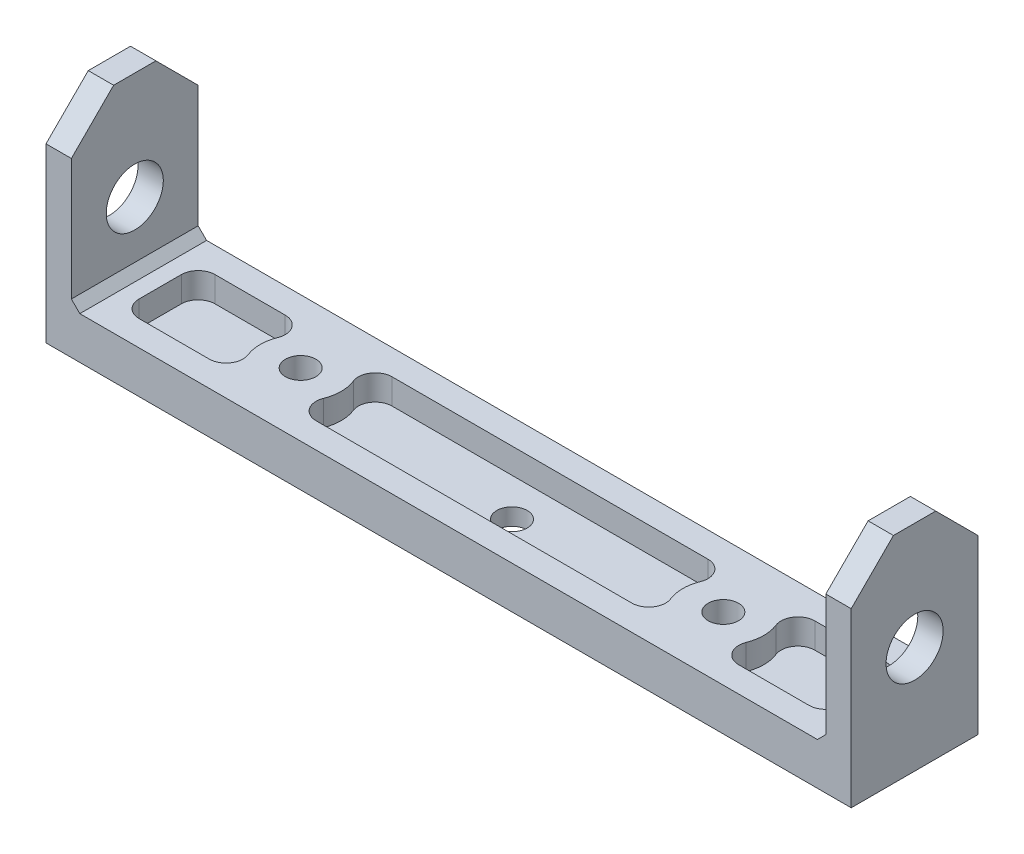
SolidWorks part; units mm, degrees
ref_plane "Front Plane" through (0, 0, 0) normal (0, 0, 1) x (1, 0, 0)
ref_plane "Top Plane" through (0, 0, 0) normal (0, 1, 0) x (1, 0, 0)
ref_plane "Right Plane" through (0, 0, 0) normal (1, 0, 0) x (0, 0, -1)
sketch "Sketch1" plane through (0, 0, 0) normal (0, 1, 0) x (1, 0, 0)
  line L1 (-47.625, -7.5) -> (47.625, -7.5)
  line L2 (-47.625, -7.5) -> (-47.625, 7.5)
  line L3 (-47.625, 7.5) -> (47.625, 7.5)
  line L4 (47.625, -7.5) -> (47.625, 7.5)
  line L5 (-47.625, -7.5) -> (47.625, 7.5) construction
  line L6 (-47.625, 7.5) -> (47.625, -7.5) construction
  point P0 (0, 0)
  dimension "D1" = 95.25
  dimension "D2" = 15
extrude "Boss-Extrude1" add sketch "Sketch1" along normal blind 5
sketch "Sketch2" plane through (0, 0, 7.5) normal (0, 0, 1) x (1, 0, 0)
  line L1 (-47.625, 0) -> (-44.625, 0)
  line L2 (-47.625, 0) -> (-47.625, 25.4)
  line L3 (-47.625, 25.4) -> (-44.625, 25.4)
  line L4 (-44.625, 0) -> (-44.625, 25.4)
  dimension "D1" = 25.4
  dimension "D2" = 3
extrude "Boss-Extrude2" add sketch "Sketch2" against normal through all
hole_wizard "1/4 Clearance Hole1" positions "Sketch3" profile "Sketch4" hole size "1/4" standard "ANSI Inch"
sketch "Sketch3" plane through (-44.625, 0, 0) normal (1, 0, 0) x (0, 0, -1)
  line L0 (-7.5, 5) -> (-7.5, 25.4) construction
  line L1 (7.5, 25.4) -> (-7.5, 25.4) construction
  point P0 (0, 12.7)
  dimension "D1" = 7.5
  dimension "D2" = 12.7
sketch "Sketch4" plane through (-44.625, 12.7, 0) normal (0, 1, 0) x (0, 0, -1)
  line L0 (0, 0) -> (0, 14.0298)
  line L1 (0, 14.0298) -> (3.3782, 12)
  line L2 (3.3782, 12) -> (3.3782, 0)
  line L5 (3.3782, 0) -> (0, 0)
  line L10 (0, 14.0298) -> (-3.3782, 12) construction
  line L11 (0, -6.35) -> (0, 107.95) construction
  dimension "Hole Dia." = 6.7564
  dimension "Hole Depth" = 12
  dimension "Drill Angle" = 118
hole_wizard "M3 Clearance Hole1" positions "Sketch7" profile "Sketch8" hole size "M3" standard "ANSI Metric"
sketch "Sketch7" plane through (0, 5, 0) normal (0, 1, 0) x (1, 0, 0)
  point P0 (-25, 0)
  point P3 (0, 0)
  point P7 (0, 0)
  point P8 (0, 0)
  dimension "D1" = 25
sketch "Sketch8" plane through (-25, 5, 0) normal (1, 0, 0) x (0, 0, 1)
  line L0 (0, 0) -> (0, 13.0815)
  line L1 (0, 13.0815) -> (1.8, 12)
  line L2 (1.8, 12) -> (1.8, 0)
  line L5 (1.8, 0) -> (0, 0)
  line L10 (0, 13.0815) -> (-1.8, 12) construction
  line L11 (0, -6.35) -> (0, 107.95) construction
  dimension "Hole Dia." = 3.6
  dimension "Hole Depth" = 12
  dimension "Drill Angle" = 118
sketch "Sketch9" plane through (0, 5, 0) normal (0, 1, 0) x (1, 0, 0)
  line L8 (44.625, 4.5) -> (-41.625, 4.5)
  line L9 (-41.625, 4.5) -> (-41.625, -4.5)
  line L10 (-41.625, -4.5) -> (44.625, -4.5)
  line L11 (44.625, -4.5) -> (44.625, 4.5)
  line L12 (44.625, 4.5) -> (-41.625, 4.5)
  line L13 (-41.625, 4.5) -> (-41.625, -4.5)
  line L14 (-41.625, -4.5) -> (44.625, -4.5)
  line L15 (44.625, -4.5) -> (44.625, 4.5)
  circle A2 centre (-25, 0) radius 4.8
  circle A3 centre (-25, 0) radius 4.8
  circle M3 centre (0, 0) radius 1.8
  dimension "D1" = 3
  dimension "D2" = 3
extrude "Cut-Extrude1" cut sketch "Sketch9" against normal blind 3 contours A3 L12 L13 L14 | A3 L14 L15 L12 M3
fillet "Fillet1" radius 2 6 edges at (-23.3297, 3.5, 4.5) (-23.3297, 3.5, -4.5) (-41.625, 3.5, 4.5) (-26.6703, 3.5, 4.5) (-26.6703, 3.5, -4.5) (-41.625, 3.5, -4.5)
chamfer "Chamfer1" distance 1 angle 45 1 edges at (-44.625, 5, 0)
chamfer "Chamfer2" distance 5 angle 45 2 edges at (-46.125, 25.4, -7.5) (-46.125, 25.4, 7.5)
sketch "Sketch10" plane through (0, 0, 7.5) normal (0, 0, 1) x (1, 0, 0)
  line L0 (-47.625, 0) -> (47.625, 0) construction
  line L1 (0, 0) -> (79.6394, 0)
  line L2 (0, 0) -> (0, 33.458)
  line L3 (0, 33.458) -> (79.6394, 33.458)
  line L4 (79.6394, 0) -> (79.6394, 33.458)
extrude "Cut-Extrude2" cut sketch "Sketch10" against normal through all
mirror "Mirror2" about plane through (0, 0, 0) normal (1, 0, 0) of bodies 108
